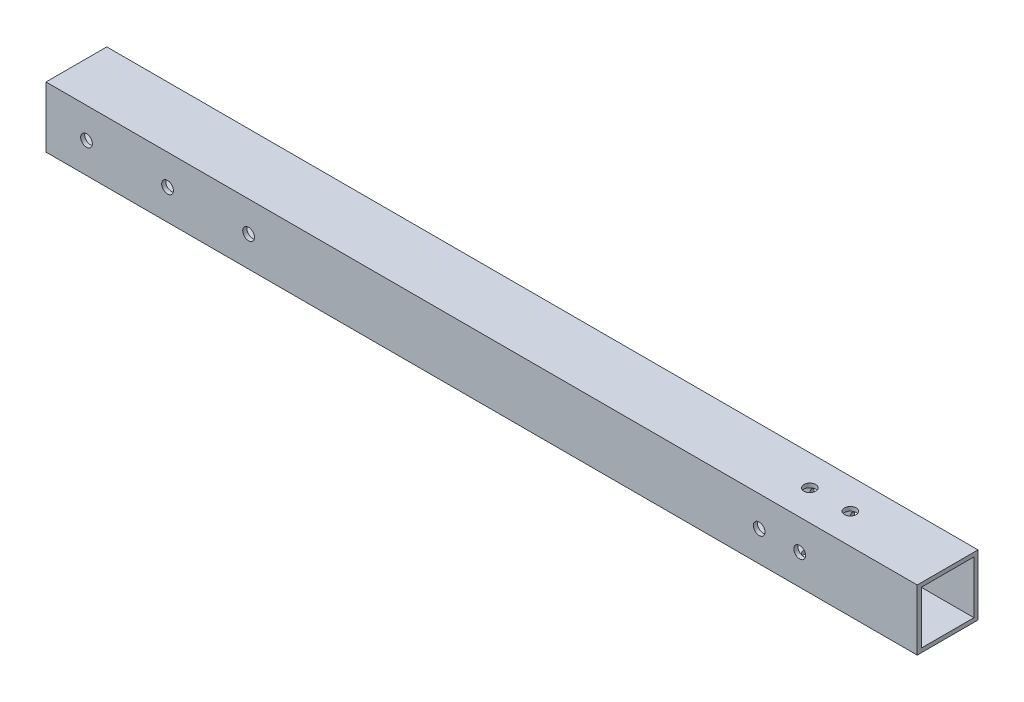
SolidWorks part; units mm, degrees
material "Thornel Mat VMA"
ref_plane "前视基准面" through (0, 0, 0) normal (0, 0, 1) x (1, 0, 0)
ref_plane "上视基准面" through (0, 0, 0) normal (0, 1, 0) x (1, 0, 0)
ref_plane "右视基准面" through (0, 0, 0) normal (1, 0, 0) x (0, 0, -1)
other "Configuration Table"
sketch "草图1" plane through (0, 0, 0) normal (1, 0, 0) x (0, 0, -1)
  line L0 (-6.5, -6.5) -> (-6.5, 6.5)
  line L1 (-7.5, -7.5) -> (7.5, -7.5)
  line L2 (-7.5, -7.5) -> (-7.5, 7.5)
  line L3 (-7.5, 7.5) -> (7.5, 7.5)
  line L4 (7.5, -7.5) -> (7.5, 7.5)
  line L5 (-7.5, -7.5) -> (7.5, 7.5) construction
  line L6 (-7.5, 7.5) -> (7.5, -7.5) construction
  line L7 (-6.5, 6.5) -> (6.5, 6.5)
  line L8 (6.5, -6.5) -> (6.5, 6.5)
  line L9 (-6.5, -6.5) -> (6.5, -6.5)
  point P0 (0, 0)
  dimension "D1" = 15
  dimension "D2" = 15
  dimension "D3" = 1
extrude "凸台-拉伸1" add sketch "草图1" along normal blind 215
sketch "草图2" plane through (0, 0, 7.5) normal (0, 0, 1) x (1, 0, 0)
  line L0 (-7.9956, 0) -> (227.7589, 0) construction
  circle A2 centre (50, 0) radius 1.45 construction
  circle A3 centre (30, 0) radius 1.45 construction
  circle A4 centre (10, 0) radius 1.45 construction
  circle A7 centre (50, 0) radius 1.45
  circle A8 centre (30, 0) radius 1.45
  circle A9 centre (10, 0) radius 1.45
  circle A10 centre (186, 0) radius 1.45
  circle A11 centre (176, 0) radius 1.45
  dimension "D1" = 2.9
  dimension "D2" = 10
  dimension "D3" = 126
extrude "切除-拉伸1" cut sketch "草图2" against normal through all
sketch "草图3" plane through (0, 7.5, 0) normal (0, 1, 0) x (1, 0, 0)
  line L0 (0, 0) -> (248.0288, 0) construction
  line L1 (215, 7.5) -> (215, -7.5) construction
  circle A4 centre (191, 0) radius 1.45
  circle A5 centre (181, 0) radius 1.45
  dimension "D1" = 24
  dimension "D2" = 10
  dimension "D3" = 2.9
extrude "切除-拉伸2" cut sketch "草图3" against normal through all
